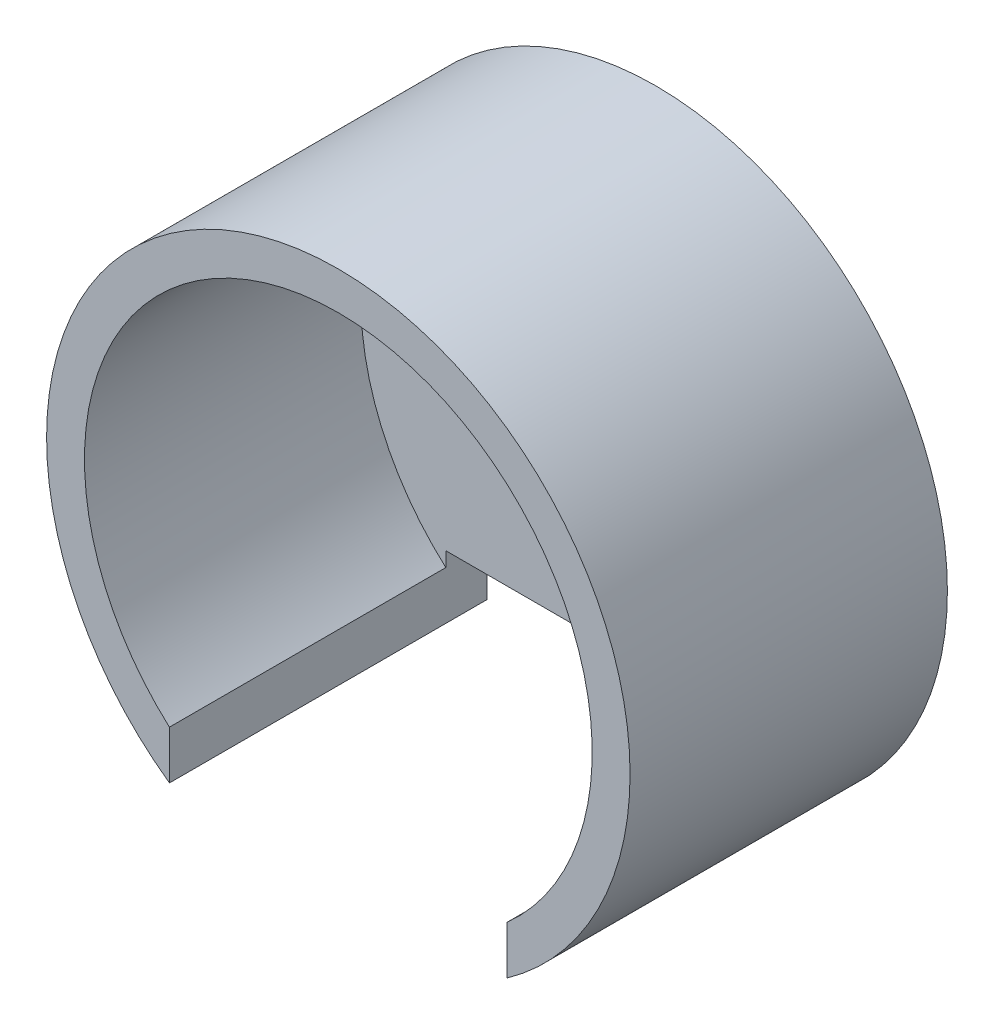
SolidWorks part; units mm, degrees
ref_plane "前视基准面" through (0, 0, 0) normal (0, 0, 1) x (1, 0, 0)
ref_plane "上视基准面" through (0, 0, 0) normal (0, 1, 0) x (1, 0, 0)
ref_plane "右视基准面" through (0, 0, 0) normal (1, 0, 0) x (0, 0, -1)
other "Configuration Table"
sketch "草图1" plane through (0, 0, 0) normal (0, 0, 1) x (1, 0, 0)
  circle A0 centre (0, 0) radius 12.4
  circle A1 centre (0, 0) radius 14.25
  dimension "D1" = 24.8
  dimension "D2" = 28.5
extrude "凸台-拉伸1" add sketch "草图1" along normal blind 13.5
sketch "草图2" plane through (0, 0, 0) normal (0, 0, -1) x (-1, 0, 0)
  line L0 (0, 0) -> (-10, 0)
  circle A0 centre (0, 0) radius 14.25
  circle A1 centre (0, 0) radius 4.5
  circle A2 centre (-10, 0) radius 1.5
  dimension "D1" = 9
  dimension "D3" = 3
  dimension "D2" = 10
extrude "凸台-拉伸2" add sketch "草图2" along normal blind 2
sketch "草图4" plane through (0, 0, 13.5) normal (0, 0, 1) x (1, 0, 0)
  line L1 (-8.25, -16.2559) -> (8.25, -16.2559)
  line L2 (-8.25, -16.2559) -> (-8.25, -8.5441)
  line L3 (-8.25, -8.5441) -> (8.25, -8.5441)
  line L4 (8.25, -16.2559) -> (8.25, -8.5441)
  line L5 (-8.25, -16.2559) -> (8.25, -8.5441) construction
  line L6 (-8.25, -8.5441) -> (8.25, -16.2559) construction
  circle A0 centre (0, 0) radius 12.4 construction
  circle A1 centre (0, 0) radius 12.4 construction
  point P0 (0, -12.4)
  dimension "D1" = 16.5
extrude "切除-拉伸2" cut sketch "草图4" against normal blind 19
